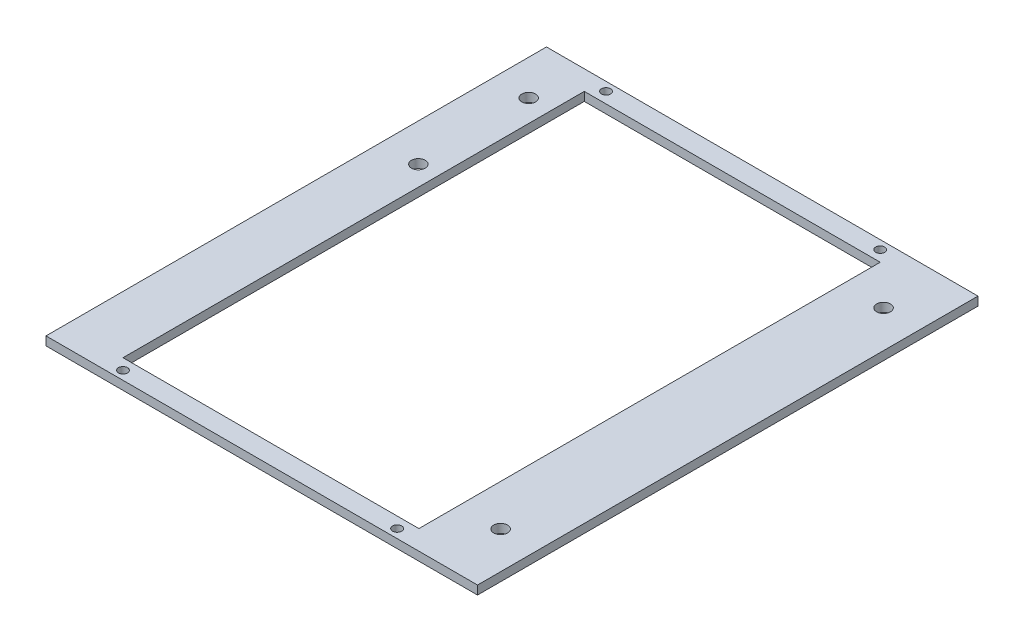
SolidWorks part; units mm, degrees
ref_plane "前视基准面" through (0, 0, 0) normal (0, 0, 1) x (1, 0, 0)
ref_plane "上视基准面" through (0, 0, 0) normal (0, 1, 0) x (1, 0, 0)
ref_plane "右视基准面" through (0, 0, 0) normal (1, 0, 0) x (0, 0, -1)
sketch "草图1" plane through (0, 0, 0) normal (0, 1, 0) x (1, 0, 0)
  line L0 (4.52, -15.78) -> (12.69, -15.78) construction
  line L1 (0, 0) -> (99.16, 0)
  line L2 (0, 0) -> (0, -115)
  line L3 (0, -115) -> (99.16, -115)
  line L4 (99.16, 0) -> (99.16, -115)
  line L5 (17.74, -23.04) -> (71.08, -23.04) construction
  line L6 (17.74, -23.04) -> (17.74, -91.62) construction
  line L7 (17.74, -91.62) -> (71.08, -91.62) construction
  line L8 (71.08, -23.04) -> (71.08, -91.62) construction
  line L9 (22.16, -27.46) -> (66.66, -27.46) construction
  line L10 (22.16, -27.46) -> (22.16, -87.2) construction
  line L11 (22.16, -87.2) -> (66.66, -87.2) construction
  line L12 (66.66, -27.46) -> (66.66, -87.2) construction
  line L13 (99.16, -8.9) -> (-0.14, -8.9) construction
  line L14 (99.16, -8.9) -> (99.16, -105.5) construction
  line L15 (99.16, -105.5) -> (-0.14, -105.5) construction
  line L16 (-0.14, -8.9) -> (-0.14, -105.5) construction
  line L17 (4.52, -8.9) -> (12.69, -8.9) construction
  line L18 (4.52, -8.9) -> (4.52, -42.03) construction
  line L19 (4.52, -42.03) -> (12.69, -42.03) construction
  line L20 (12.69, -8.9) -> (12.69, -42.03) construction
  line L21 (4.52, -34.06) -> (12.69, -34.06) construction
  line L23 (13.69, 0) -> (80.69, 0) construction
  line L24 (13.69, 0) -> (13.69, -115) construction
  line L25 (13.69, -115) -> (80.69, -115) construction
  line L26 (80.69, 0) -> (80.69, -115) construction
  line L27 (15.69, -2) -> (78.69, -2) construction
  line L28 (15.69, -2) -> (15.69, -113) construction
  line L29 (15.69, -113) -> (78.69, -113) construction
  line L30 (78.69, -2) -> (78.69, -113) construction
  line L31 (4.52, -8.9) -> (12.69, -8.9)
  line L32 (4.52, -8.9) -> (4.52, -15.78)
  line L33 (4.52, -15.78) -> (12.69, -15.78)
  line L34 (12.69, -8.9) -> (12.69, -15.78)
  line L35 (4.52, -34.06) -> (12.69, -34.06)
  line L36 (4.52, -34.06) -> (4.52, -42.03)
  line L37 (4.52, -42.03) -> (12.69, -42.03)
  line L38 (12.69, -34.06) -> (12.69, -42.03)
  line L43 (13.19, -4.5) -> (81.19, -4.5)
  line L44 (13.19, -4.5) -> (13.19, -110.5)
  line L45 (13.19, -110.5) -> (81.19, -110.5)
  line L46 (81.19, -4.5) -> (81.19, -110.5)
  circle A0 centre (22.16, -27.46) radius 1.585
  circle A1 centre (66.66, -27.46) radius 1.585
  circle A2 centre (22.16, -87.2) radius 1.585
  circle A3 centre (66.66, -87.2) radius 1.585
  circle A4 centre (90.66, -13.2) radius 1.585
  circle A5 centre (90.66, -101.2) radius 1.585
  circle A6 centre (8.12, -12.2) radius 1.585
  circle A7 centre (8.62, -38.06) radius 1.585
  circle A8 centre (15.69, -2) radius 1.05
  circle A9 centre (78.69, -2) radius 1.05
  circle A10 centre (15.69, -113) radius 1.05
  circle A11 centre (78.69, -113) radius 1.05
  dimension "D11" = 3.17
  dimension "D12" = 3.17
  dimension "D13" = 3.17
  dimension "D14" = 3.17
  dimension "D19" = 3.17
  dimension "D22" = 3.17
  dimension "D30" = 3.17
  dimension "D33" = 3.17
  dimension "D42" = 2.1
  dimension "D43" = 2.1
  dimension "D44" = 2.1
  dimension "D45" = 2.1
  dimension "D2" = 115
  dimension "D3" = 53.34
  dimension "D4" = 68.58
  dimension "D5" = 4.42
  dimension "D6" = 4.42
  dimension "D7" = 4.42
  dimension "D8" = 4.42
  dimension "D9" = 99.3
  dimension "D10" = 96.6
  dimension "D15" = 68.5
  dimension "D16" = 74
  dimension "D17" = 18.3
  dimension "D18" = 22.3
  dimension "D20" = 68.5
  dimension "D21" = 14
  dimension "D23" = 94.64
  dimension "D24" = 8.17
  dimension "D25" = 6.88
  dimension "D26" = 18.28
  dimension "D27" = 7.97
  dimension "D28" = 3.6
  dimension "D29" = 3.3
  dimension "D31" = 4.1
  dimension "D32" = 4
  dimension "D34" = 9.5
  dimension "D35" = 2
  dimension "D36" = 2
  dimension "D37" = 2
  dimension "D38" = 2
  dimension "D39" = 67
  dimension "D40" = 115
  dimension "D41" = 1
  dimension "D46" = 99.16
  dimension "D47" = 4.5
  dimension "D48" = 4.5
  dimension "D49" = 0.5
  dimension "D50" = 0.5
extrude "凸台-拉伸1" add sketch "草图1" along normal blind 2 contours L4 L1 L2 L3 A11 A10 A9 A8 A5 A4 A3 A2 A1 A0 | L32 L33 L2 L31 A6 | L36 L37 L2 L35 A7
